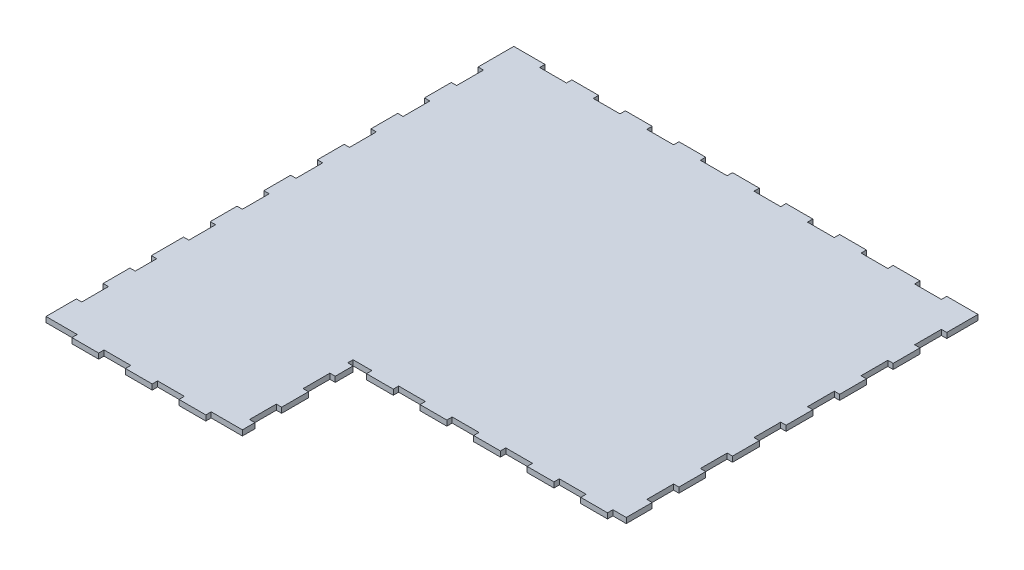
SolidWorks part; units mm, degrees
ref_plane "Alzado" through (0, 0, 0) normal (0, 0, 1) x (1, 0, 0)
ref_plane "Planta" through (0, 0, 0) normal (0, 1, 0) x (1, 0, 0)
ref_plane "Vista lateral" through (0, 0, 0) normal (1, 0, 0) x (0, 0, -1)
sketch "Croquis1" plane through (0, 0, 0) normal (0, 1, 0) x (1, 0, 0)
  line L0 (17.5, 0) -> (32.5, 0)
  line L1 (0, 3) -> (0, 20)
  line L2 (0, 265) -> (17.5, 265)
  line L3 (260, 265) -> (260, 247.5)
  line L4 (252.5, 65) -> (237.5, 65)
  line L5 (110, 65) -> (110, 55)
  line L6 (110, 3) -> (110, 10)
  line L8 (47.5, 0) -> (47.5, 3)
  line L9 (47.5, 3) -> (32.5, 3)
  line L10 (32.5, 3) -> (32.5, 0)
  line L12 (17.5, 0) -> (17.5, 3)
  line L13 (17.5, 3) -> (0, 3)
  line L15 (92.5, 3) -> (110, 3)
  line L16 (92.5, 0) -> (92.5, 3)
  line L17 (77.5, 3) -> (77.5, 0)
  line L18 (62.5, 3) -> (77.5, 3)
  line L19 (62.5, 0) -> (62.5, 3)
  line L20 (110, 25) -> (107, 25)
  line L21 (107, 25) -> (107, 10)
  line L22 (107, 10) -> (110, 10)
  line L24 (107, 55) -> (110, 55)
  line L25 (107, 40) -> (107, 55)
  line L26 (110, 40) -> (107, 40)
  line L28 (177.5, 65) -> (177.5, 68)
  line L29 (177.5, 68) -> (162.5, 68)
  line L30 (162.5, 68) -> (162.5, 65)
  line L31 (162.5, 65) -> (147.5, 65)
  line L32 (147.5, 65) -> (147.5, 68)
  line L33 (147.5, 68) -> (132.5, 68)
  line L34 (132.5, 68) -> (132.5, 65)
  line L35 (132.5, 65) -> (117.5, 65)
  line L36 (117.5, 65) -> (117.5, 68)
  line L37 (117.5, 68) -> (107, 68)
  line L38 (107, 68) -> (107, 65)
  line L39 (107, 65) -> (110, 65)
  line L41 (260, 157.5) -> (257, 157.5)
  line L42 (252.5, 68) -> (260, 68)
  line L43 (252.5, 65) -> (252.5, 68)
  line L44 (237.5, 68) -> (237.5, 65)
  line L45 (222.5, 68) -> (237.5, 68)
  line L46 (222.5, 65) -> (222.5, 68)
  line L47 (207.5, 68) -> (207.5, 65)
  line L48 (192.5, 68) -> (207.5, 68)
  line L49 (192.5, 65) -> (192.5, 68)
  line L50 (257, 157.5) -> (257, 142.5)
  line L51 (257, 142.5) -> (260, 142.5)
  line L52 (260, 142.5) -> (260, 127.5)
  line L53 (260, 127.5) -> (257, 127.5)
  line L54 (257, 127.5) -> (257, 112.5)
  line L55 (257, 112.5) -> (260, 112.5)
  line L56 (260, 112.5) -> (260, 97.5)
  line L57 (260, 97.5) -> (257, 97.5)
  line L58 (257, 97.5) -> (257, 82.5)
  line L59 (257, 82.5) -> (260, 82.5)
  line L61 (257, 247.5) -> (260, 247.5)
  line L62 (257, 232.5) -> (257, 247.5)
  line L63 (260, 232.5) -> (257, 232.5)
  line L64 (257, 217.5) -> (260, 217.5)
  line L65 (257, 202.5) -> (257, 217.5)
  line L66 (260, 202.5) -> (257, 202.5)
  line L67 (257, 187.5) -> (260, 187.5)
  line L68 (257, 172.5) -> (257, 187.5)
  line L69 (260, 172.5) -> (257, 172.5)
  line L70 (137.5, 265) -> (137.5, 262)
  line L71 (137.5, 262) -> (152.5, 262)
  line L72 (152.5, 262) -> (152.5, 265)
  line L73 (152.5, 265) -> (167.5, 265)
  line L74 (167.5, 265) -> (167.5, 262)
  line L75 (167.5, 262) -> (182.5, 262)
  line L76 (182.5, 262) -> (182.5, 265)
  line L77 (182.5, 265) -> (197.5, 265)
  line L78 (197.5, 265) -> (197.5, 262)
  line L79 (197.5, 262) -> (212.5, 262)
  line L80 (212.5, 262) -> (212.5, 265)
  line L81 (212.5, 265) -> (227.5, 265)
  line L82 (227.5, 265) -> (227.5, 262)
  line L83 (227.5, 262) -> (242.5, 262)
  line L84 (242.5, 262) -> (242.5, 265)
  line L86 (17.5, 262) -> (17.5, 265)
  line L87 (32.5, 262) -> (17.5, 262)
  line L88 (32.5, 265) -> (32.5, 262)
  line L89 (47.5, 262) -> (47.5, 265)
  line L90 (62.5, 262) -> (47.5, 262)
  line L91 (62.5, 265) -> (62.5, 262)
  line L92 (77.5, 262) -> (77.5, 265)
  line L93 (92.5, 262) -> (77.5, 262)
  line L94 (92.5, 265) -> (92.5, 262)
  line L95 (107.5, 262) -> (107.5, 265)
  line L96 (122.5, 262) -> (107.5, 262)
  line L97 (122.5, 265) -> (122.5, 262)
  line L98 (0, 140) -> (3, 140)
  line L99 (3, 140) -> (3, 155)
  line L100 (3, 155) -> (0, 155)
  line L101 (0, 155) -> (0, 170)
  line L102 (0, 170) -> (3, 170)
  line L103 (3, 170) -> (3, 185)
  line L104 (3, 185) -> (0, 185)
  line L105 (0, 185) -> (0, 200)
  line L106 (0, 200) -> (3, 200)
  line L107 (3, 200) -> (3, 215)
  line L108 (3, 215) -> (0, 215)
  line L109 (0, 215) -> (0, 230)
  line L110 (0, 230) -> (3, 230)
  line L111 (3, 230) -> (3, 245)
  line L112 (3, 245) -> (0, 245)
  line L114 (3, 20) -> (0, 20)
  line L115 (3, 35) -> (3, 20)
  line L116 (0, 35) -> (3, 35)
  line L117 (3, 50) -> (0, 50)
  line L118 (3, 62) -> (3, 50)
  line L119 (32.5, 265) -> (47.5, 265)
  line L120 (3, 80) -> (0, 80)
  line L121 (3, 95) -> (3, 80)
  line L122 (0, 95) -> (3, 95)
  line L123 (3, 110) -> (0, 110)
  line L124 (3, 125) -> (3, 110)
  line L125 (0, 125) -> (3, 125)
  line L127 (0, 62) -> (3, 62)
  line L128 (62.5, 265) -> (77.5, 265)
  line L129 (92.5, 265) -> (107.5, 265)
  line L130 (122.5, 265) -> (137.5, 265)
  line L134 (242.5, 265) -> (260, 265)
  line L135 (0, 245) -> (0, 265)
  line L139 (0, 125) -> (0, 140)
  line L140 (0, 95) -> (0, 110)
  line L141 (0, 62) -> (0, 80)
  line L142 (0, 35) -> (0, 50)
  line L143 (47.5, 0) -> (62.5, 0)
  line L144 (77.5, 0) -> (92.5, 0)
  line L147 (110, 40) -> (110, 25)
  line L150 (192.5, 65) -> (177.5, 65)
  line L151 (222.5, 65) -> (207.5, 65)
  line L152 (260, 82.5) -> (260, 68)
  line L155 (260, 172.5) -> (260, 157.5)
  line L156 (260, 202.5) -> (260, 187.5)
  line L157 (260, 232.5) -> (260, 217.5)
  dimension "D5" = 3
  dimension "D6" = 15
  dimension "D7" = 15
  dimension "D9" = 3
  dimension "D10" = 15
  dimension "D12" = 3
  dimension "D13" = 15
  dimension "D14" = 15
  dimension "D15" = 15
  dimension "D16" = 15
  dimension "D18" = 3
  dimension "D19" = 15
  dimension "D20" = 15
  dimension "D21" = 15
  dimension "D22" = 15
  dimension "D23" = 15
  dimension "D25" = 3
  dimension "D26" = 15
  dimension "D27" = 15
  dimension "D28" = 15
  dimension "D29" = 15
  dimension "D30" = 15
  dimension "D31" = 15
  dimension "D32" = 15
  dimension "D34" = 3
  dimension "D35" = 15
  dimension "D36" = 15
  dimension "D37" = 15
  dimension "D38" = 15
  dimension "D39" = 15
  dimension "D40" = 15
  dimension "D41" = 15
extrude "Saliente-Extruir1" add sketch "Croquis1" along normal blind 3
